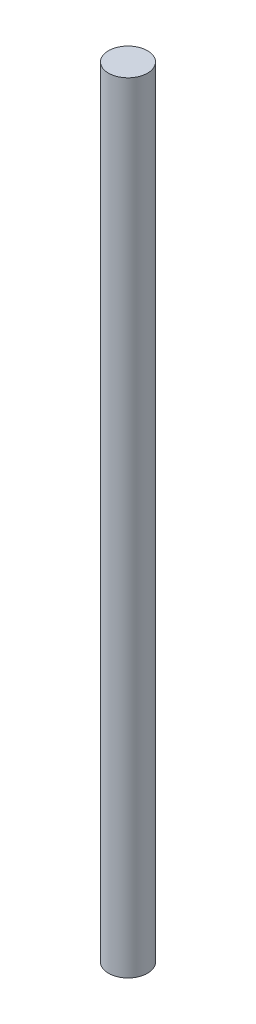
SolidWorks part; units mm, degrees
ref_plane "Plan de face" through (0, 0, 0) normal (0, 0, 1) x (1, 0, 0)
ref_plane "Plan de dessus" through (0, 0, 0) normal (0, 1, 0) x (1, 0, 0)
ref_plane "Plan de droite" through (0, 0, 0) normal (1, 0, 0) x (0, 0, -1)
sketch "Esquisse1" plane through (0, 0, 0) normal (0, 1, 0) x (1, 0, 0)
  circle A0 centre (0, 0) radius 3
  dimension "D1" = 6
extrude "Boss.-Extru.1" add sketch "Esquisse1" along normal blind 120
